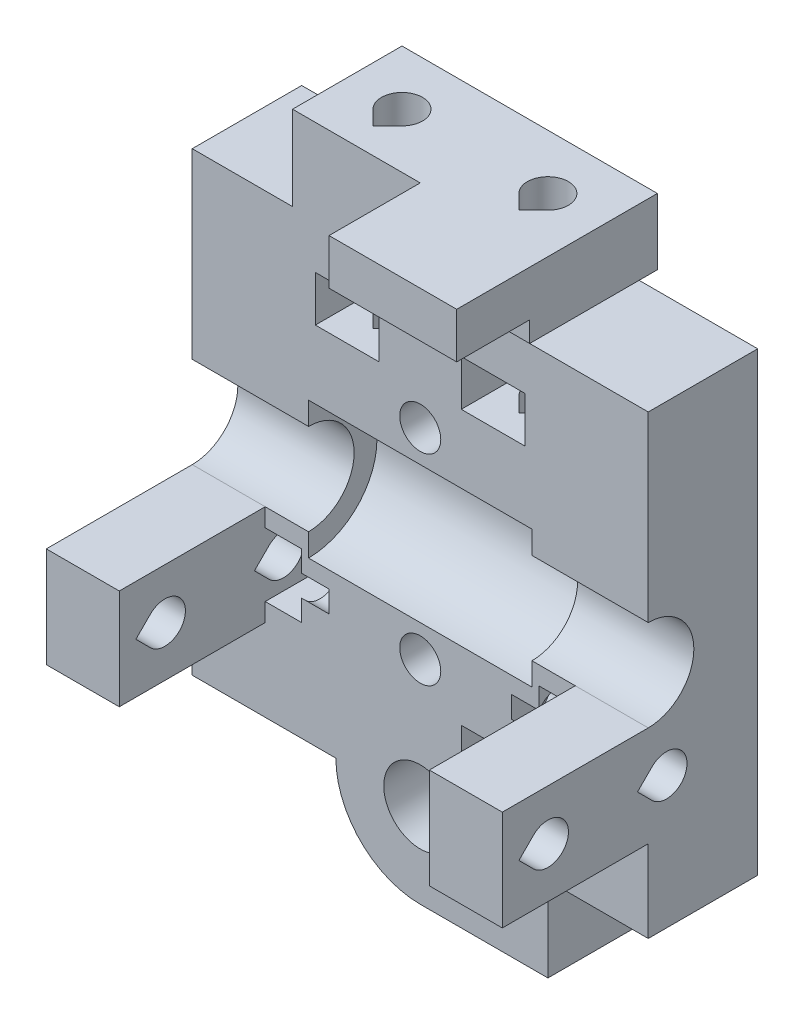
SolidWorks part; units mm, degrees
material "Printed PLA"
ref_plane "Front Plane" through (0, 0, 0) normal (0, 0, 1) x (1, 0, 0)
ref_plane "Top Plane" through (0, 0, 0) normal (0, 1, 0) x (1, 0, 0)
ref_plane "Right Plane" through (0, 0, 0) normal (1, 0, 0) x (0, 0, -1)
sketch "Sketch1" plane through (0, 0, 0) normal (0, 0, 1) x (1, 0, 0)
  line L0 (25, -25) -> (-25, 25) construction
  line L1 (-25, 25) -> (25, 25)
  line L2 (-25, 25) -> (-25, -25)
  line L3 (-25, -25) -> (25, -25)
  line L4 (25, 25) -> (25, -25)
  dimension "D1" = 50
  dimension "D2" = 50
extrude "Boss-Extrude1" add sketch "Sketch1" along normal blind 12
sketch "Sketch2" plane through (-25, 0, 0) normal (-1, 0, 0) x (0, 0, 1)
  line L0 (12, 25) -> (12, -25) construction
  circle A0 centre (12, 0) radius 5
  dimension "D1" = 10
extrude "Cut-Extrude1" cut sketch "Sketch2" against normal through all
sketch "Sketch3" plane through (-25, 0, 0) normal (-1, 0, 0) x (0, 0, 1)
  circle A0 centre (12, 0) radius 7.5
  dimension "D1" = 15
extrude "Cut-Extrude2" cut sketch "Sketch3" against normal blind 24.5 from offset 12.75 offset against normal yes
sketch "Sketch4" plane through (0, 0, 12) normal (0, 0, 1) x (1, 0, 0)
  line L0 (0, -11) -> (0, 11) construction
  line L1 (0, 7.5) -> (0, -11) construction
  line L2 (12.25, 7.5) -> (-12.25, 7.5) construction
  line L3 (0, 11) -> (-25, 0) construction
  line L4 (-25, 0) -> (0, -11) construction
  line L5 (-25, 5) -> (-25, -5) construction
  circle A0 centre (0, 11) radius 2.25
  circle A1 centre (0, -11) radius 2.25
  dimension "D2" = 4.5
  dimension "D1" = 22
extrude "Cut-Extrude3" cut sketch "Sketch4" against normal through all
sketch "Sketch5" plane through (0, 0, 12) normal (0, 0, 1) x (1, 0, 0)
  line L0 (25, 25) -> (-25, 25) construction
  line L1 (-25, -25) -> (25, -25) construction
  line L2 (0, -25) -> (0, 25) construction
  line L3 (25, 5) -> (25, 25) construction
  circle A0 centre (0, 25) radius 4
  circle A1 centre (0, -25) radius 4
  dimension "D1" = 8
  dimension "D2" = 25
extrude "Cut-Extrude4" cut sketch "Sketch5" against normal through all
sketch "Sketch11" plane through (0, 0, 12) normal (0, 0, 1) x (1, 0, 0)
  line L0 (3.4641, 27) -> (14, 27)
  line L1 (14, 27) -> (14, 34.25)
  line L2 (14, 34.25) -> (0, 34.25)
  line L3 (-4, 25) -> (-25, 25) construction
  line L4 (-9.25, 25) -> (-4, 25)
  line L5 (25, 25) -> (4, 25) construction
  arc A0 (-4, 25) -> (3.4641, 27) centre (0, 25) cw
  arc A1 (-4, 25) -> (4, 25) centre (0, 25) ccw construction
  arc A2 (0, 34.25) -> (-9.25, 25) centre (0, 25) ccw
  dimension "D1" = 5.25
  dimension "D2" = 14
  dimension "D3" = 2
extrude "Boss-Extrude3" add sketch "Sketch11" against normal up to surface (12 mm away) up to face at (2.25, -11, 0)
sketch "Sketch6" plane through (0, 25, 0) normal (0, 1, 0) x (1, 0, 0)
  line L0 (6.409, -7.591) -> (8, -9.182)
  line L1 (8, -9.182) -> (9.591, -7.591)
  line L2 (8, -9.182) -> (8, -6) construction
  line L3 (8, -6) -> (4, -6) construction
  line L4 (4, 0) -> (4, -12) construction
  line L5 (0, 0) -> (0, -12) construction
  line L6 (4, 0) -> (-4, 0) construction
  line L7 (-4, -12) -> (4, -12) construction
  line L8 (-8, -6) -> (-4, -6) construction
  line L9 (-8, -9.182) -> (-8, -6) construction
  line L10 (-8, -9.182) -> (-9.591, -7.591) construction
  line L11 (-6.409, -7.591) -> (-8, -9.182) construction
  arc A0 (9.591, -7.591) -> (6.409, -7.591) centre (8, -6) ccw
  arc A1 (-9.591, -7.591) -> (-6.409, -7.591) centre (-8, -6) cw construction
  dimension "D1" = 4.5
  dimension "D2" = 16
extrude "Cut-Extrude5" cut sketch "Sketch6" against normal blind 15 and the other way through all
sketch "Sketch7" plane through (0, 0, 12) normal (0, 0, 1) x (1, 0, 0)
  line L0 (8, 20) -> (8, 15) construction
  line L1 (-11.5, 20) -> (-4.5, 20) construction
  line L2 (-11.5, 20) -> (-11.5, 15) construction
  line L3 (-11.5, 15) -> (-4.5, 15) construction
  line L4 (-4.5, 20) -> (-4.5, 15) construction
  line L5 (4.5, 20) -> (11.5, 20)
  line L6 (4.5, 20) -> (4.5, 15)
  line L7 (4.5, 15) -> (11.5, 15)
  line L8 (11.5, 20) -> (11.5, 15)
  line L9 (-8, 20) -> (-8, 15) construction
  line L10 (0, 21) -> (0, 25) construction
  line L11 (25, 25) -> (4, 25) construction
  dimension "D1" = 7
  dimension "D2" = 5
  dimension "D3" = 16
  dimension "D4" = 5
extrude "Cut-Extrude6" cut sketch "Sketch7" against normal through all
sketch "Sketch13" plane through (0, 0, 12) normal (0, 0, 1) x (1, 0, 0)
  line L0 (3.4641, 27) -> (14, 27) construction
  line L1 (14, 34.25) -> (4, 34.25)
  line L2 (14, 34.25) -> (14, 27)
  line L3 (14, 27) -> (4, 27)
  line L4 (4, 34.25) -> (4, 27)
  arc A0 (3.4641, 27) -> (4, 25) centre (0, 25) ccw construction
extrude "Boss-Extrude4" add sketch "Sketch13" along normal blind 2
sketch "Sketch14" plane through (0, 0, 12) normal (0, 0, 1) x (1, 0, 0)
  line L1 (14, 34.25) -> (0, 34.25)
  line L2 (14, 34.25) -> (14, 29.25)
  line L3 (14, 29.25) -> (0, 29.25)
  line L4 (0, 34.25) -> (0, 29.25)
  dimension "D1" = 5
extrude "Boss-Extrude5" add sketch "Sketch14" along normal blind 10
mirror "Mirror1" about plane through (0, 0, 0) normal (0, 1, 0) of "Boss-Extrude5", "Boss-Extrude3", "Cut-Extrude5", "Cut-Extrude6", "Boss-Extrude4"
sketch "Sketch8" plane through (-25, 0, 0) normal (-1, 0, 0) x (0, 0, 1)
  line L1 (12, -5) -> (28, -5)
  line L2 (12, -5) -> (12, -16)
  line L3 (12, -16) -> (28, -16)
  line L4 (28, -5) -> (28, -16)
  dimension "D1" = 11
  dimension "D2" = 16
extrude "Boss-Extrude2" add sketch "Sketch8" against normal blind 8
sketch "Sketch9" plane through (-25, 0, 0) normal (-1, 0, 0) x (0, 0, 1)
  line L0 (28, -10.5) -> (23, -10.5) construction
  line L1 (28, -16) -> (28, -5) construction
  line L2 (23, -10.5) -> (10, -10.5) construction
  line L3 (11.591, -8.909) -> (13.182, -10.5)
  line L4 (13.182, -10.5) -> (11.591, -12.091)
  line L5 (24.591, -8.909) -> (26.182, -10.5)
  line L6 (26.182, -10.5) -> (24.591, -12.091)
  arc A0 (11.591, -8.909) -> (11.591, -12.091) centre (10, -10.5) ccw
  arc A1 (24.591, -8.909) -> (24.591, -12.091) centre (23, -10.5) ccw
  arc A2 (12, 5) -> (12, -5) centre (12, 0) ccw construction
  dimension "D1" = 4.5
  dimension "D3" = 11
  dimension "D2" = 13
extrude "Cut-Extrude7" cut sketch "Sketch9" against normal blind 15
sketch "Sketch10" plane through (0, 0, 12) normal (0, 0, 1) x (1, 0, 0)
  line L0 (-17, -5) -> (-17, -9.318) construction
  line L1 (-17, -7) -> (-13, -7)
  line L2 (-17, -7) -> (-17, -14)
  line L3 (-17, -14) -> (-13, -14)
  line L4 (-13, -7) -> (-13, -14)
  line L5 (-17, -10.5) -> (-13, -10.5) construction
  line L6 (-17, -16) -> (-17, -5) construction
  dimension "D1" = 4
  dimension "D2" = 7
extrude "Cut-Extrude8" cut sketch "Sketch10" against normal blind 7
mirror "Mirror2" about plane through (0, 0, 0) normal (1, 0, 0) of "Cut-Extrude7", "Cut-Extrude8", "Boss-Extrude2"
sketch "Sketch12" plane through (0, -34.25, 0) normal (0, 1, 0) x (1, 0, 0)
  line L0 (5.1716, -8.8284) -> (8, -11.6569)
  line L1 (8, -11.6569) -> (10.8284, -8.8284)
  line L2 (8, -11.6569) -> (8, -6) construction
  arc A0 (10.8284, -8.8284) -> (5.1716, -8.8284) centre (8, -6) ccw
  dimension "D1" = 4
extrude "Cut-Extrude9" cut sketch "Sketch12" along normal blind 4
sketch "Sketch15" plane through (0, 0, 12) normal (0, 0, 1) x (1, 0, 0)
  line L1 (-11.5, 20) -> (-4.5, 20)
  line L2 (-11.5, 20) -> (-11.5, 15)
  line L3 (-11.5, 15) -> (-4.5, 15)
  line L4 (-4.5, 20) -> (-4.5, 15)
extrude "Cut-Extrude10" cut sketch "Sketch15" against normal through all
sketch "Sketch16" plane through (0, 0, 12) normal (0, 0, 1) x (1, 0, 0)
  line L0 (-9.25, 25) -> (-25, 25) construction
  line L1 (-14, 25) -> (-4, 25)
  line L2 (-14, 25) -> (-14, 34.25)
  line L3 (-14, 34.25) -> (0, 34.25)
  line L4 (0, 29) -> (0, 34.25)
  line L5 (14, 27) -> (8, 20) construction
  line L6 (-8, 20) -> (-14, 27) construction
  line L7 (-14, 27) -> (14, 27) construction
  line L8 (0, 34.25) -> (0, 29.25) construction
  line L9 (0, 34.25) -> (0, 29.25) construction
  arc A0 (0, 34.25) -> (-9.25, 25) centre (0, 25) ccw construction
  arc A1 (0, 29) -> (-4, 25) centre (0, 25) ccw
  arc A2 (3.4641, 27) -> (4, 25) centre (0, 25) ccw construction
extrude "Boss-Extrude6" add sketch "Sketch16" against normal up to surface (12 mm away) contours L2 L3 L4 A1 L1 up to face at (-8, 17.5, 0)
sketch "Sketch17" plane through (0, 34.25, 0) normal (0, 1, 0) x (1, 0, 0)
  line L1 (-9.591, -7.591) -> (-8, -9.182)
  line L2 (-8, -9.182) -> (-6.409, -7.591)
  arc A0 (-6.409, -7.591) -> (-9.591, -7.591) centre (-8, -6) ccw
extrude "Cut-Extrude11" cut sketch "Sketch17" against normal up to surface (24.25 mm away) up to face at (8, 10, 6.841)
sketch "Sketch18" plane through (14, 0, 0) normal (1, 0, 0) x (0, 0, -1)
  line L1 (-12, -16) -> (-22, -16)
  line L2 (-12, -16) -> (-12, -34.25)
  line L3 (-12, -34.25) -> (-22, -34.25)
  line L4 (-22, -16) -> (-22, -34.25)
extrude "Cut-Extrude12" cut sketch "Sketch18" against normal through all
